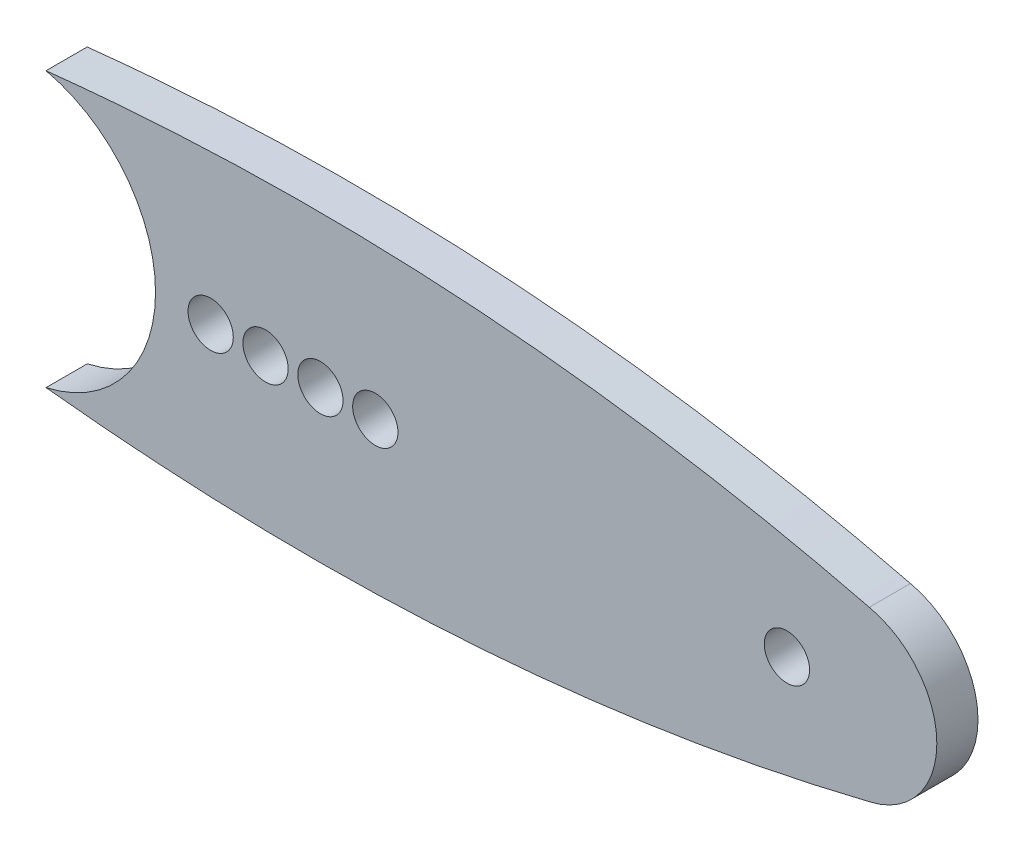
SolidWorks part; units mm, degrees
ref_plane "Front Plane" through (0, 0, 0) normal (0, 0, 1) x (1, 0, 0)
ref_plane "Top Plane" through (0, 0, 0) normal (0, 1, 0) x (1, 0, 0)
ref_plane "Right Plane" through (0, 0, 0) normal (1, 0, 0) x (0, 0, -1)
sketch "Sketch1" plane through (0, 0, 0) normal (0, 0, 1) x (1, 0, 0)
  line L0 (0, 0) -> (64.9249, 0) construction
  circle A0 centre (12, 0) radius 1.65
  circle A1 centre (16, 0) radius 1.65
  circle A2 centre (20, 0) radius 1.65
  circle A3 centre (24, 0) radius 1.65
  circle A4 centre (54, 0) radius 1.65
  arc A6 (60, 6.136) -> (60, -6.136) centre (58.64, 0) cw
  arc A7 (0, 10) -> (0, -10) centre (-2.273, 0) cw
  spline S0 degree 2 poles (0, 10) (30.8925, 13.3371) (60, 6.136) knots 0 0 0 0.860506 0.860506 0.860506
  spline S1 degree 2 poles (0, -10) (30.8925, -13.3371) (60, -6.136) knots 0 0 0 0.860506 0.860506 0.860506
  point P25 (64.9249, 0)
  dimension "D4" = 3.3
  dimension "D3" = 54
extrude "Boss-Extrude1" add sketch "Sketch1" along normal blind 3
sketch "Sketch2" plane through (0, 0, 0) normal (0, 0, -1) x (-1, 0, 0)
  line L0 (-64.9249, 0) -> (-28, 0) construction
  arc A0 (-60, 6.136) -> (-60, -6.136) centre (-58.64, 0) ccw construction
  arc A1 (-24, 4) -> (-24, -4) centre (-24, 0) ccw construction
sketch "Sketch3" plane through (0, 0, 0) normal (0, 0, -1) x (-1, 0, 0)
  line L0 (-64.9249, 0) -> (-28, 0) construction
  line L1 (-49.2337, -1.7632) -> (-29.2337, -1.7632)
  line L2 (-49.2337, -1.7632) -> (-49.2337, 1.7632)
  line L3 (-49.2337, 1.7632) -> (-29.2337, 1.7632)
  line L4 (-29.2337, -1.7632) -> (-29.2337, 1.7632)
  line L5 (-49.2337, -1.7632) -> (-29.2337, 1.7632) construction
  line L6 (-49.2337, 1.7632) -> (-29.2337, -1.7632) construction
  point P0 (-39.2337, 0)
  dimension "D1" = 20
extrude "Boss-Extrude2" add sketch "Sketch3" along normal blind 3
